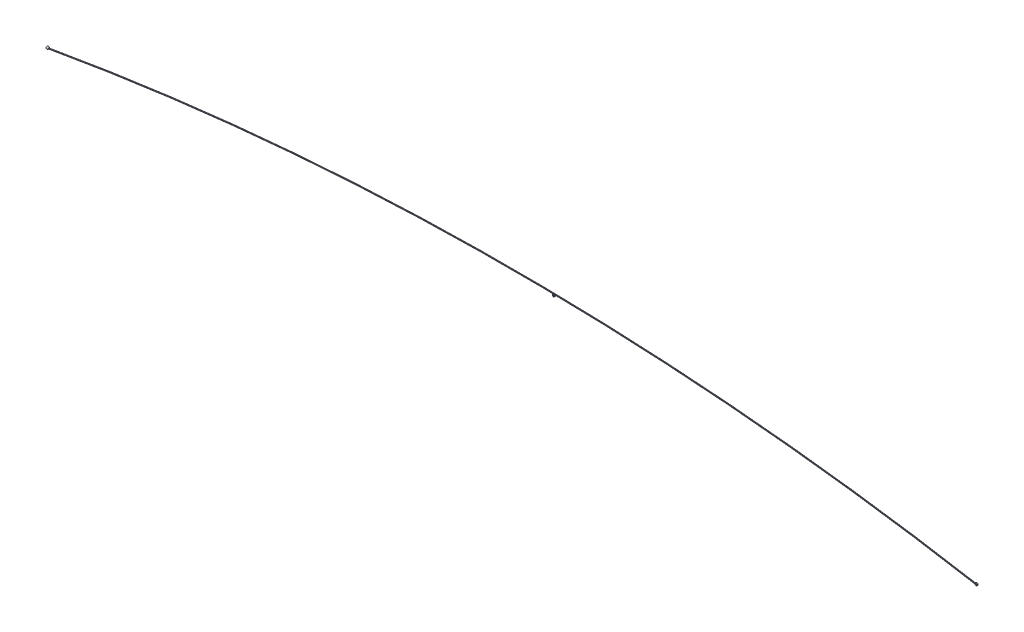
SolidWorks part; units mm, degrees
ref_plane "Alzado" through (0, 0, 0) normal (0, 0, 1) x (1, 0, 0)
ref_plane "Planta" through (0, 0, 0) normal (0, 1, 0) x (1, 0, 0)
ref_plane "Vista lateral" through (0, 0, 0) normal (1, 0, 0) x (0, 0, -1)
sketch "Croquis1" plane through (0, 0, 0) normal (0, 0, 1) x (1, 0, 0)
  line L0 (0, 0) -> (-980, 0) construction
  arc A0 (-980, 0) -> (0, 0) centre (-490, -2766.9478) cw
  dimension "D2" = 2810
  dimension "D1" = 980
sketch "Croquis2" plane through (0, 0, 0) normal (1, 0, 0) x (0, 0, -1)
  line L0 (0, 0.5) -> (-0.433, 0.25)
  line L1 (-0.433, 0.25) -> (-0.433, -0.25)
  line L2 (-0.433, -0.25) -> (0, -0.5)
  line L3 (0, -0.5) -> (0.433, -0.25)
  line L4 (0.433, -0.25) -> (0.433, 0.25)
  line L5 (0.433, 0.25) -> (0, 0.5)
  line L6 (0, -0.5) -> (0, 0.5) construction
  line L7 (0, 0.0077) -> (0.0067, 0.0039) construction
  line L8 (0.433, 0.25) -> (-0.433, -0.25) construction
  point P1 (0, 0)
  dimension "D1" = 0.5
  dimension "D2" = 0.5
sweep "Barrer1" add profiles "Croquis2" path "Croquis1"
sketch "Croquis3" plane through (0, 0, 0) normal (0, 0, 1) x (1, 0, 0)
  line L0 (-981.75, 0.25) -> (-979.25, 0.25) construction
  line L1 (-981.75, 0.25) -> (-979.25, 0.25)
  arc A0 (-979.25, 0.25) -> (-981.75, 0.25) centre (-980.5, 0.25) ccw
  dimension "D1" = 2.5
  dimension "D2" = 980.5
revolve "Revolución1" add sketch "Croquis3" angle 360 about L0
sketch "Croquis4" plane through (0, 0, 0) normal (0, 0, 1) x (1, 0, 0)
  circle A0 centre (1, 0) radius 1.25
  circle A1 centre (1, 0) radius 0.75
  circle A2 centre (-445.44, 41.2) radius 1.25
  circle A3 centre (-445.44, 41.2) radius 0.75
  dimension "D1" = 2.5
  dimension "D2" = 1.5
  dimension "D4" = 2.5
  dimension "D5" = 1.5
  dimension "D3" = 1
  dimension "D6" = 446.44
  dimension "D7" = 41.2
extrude "Saliente-Extruir1" add sketch "Croquis4" along normal blind 0.5 and the other way blind 0.5
